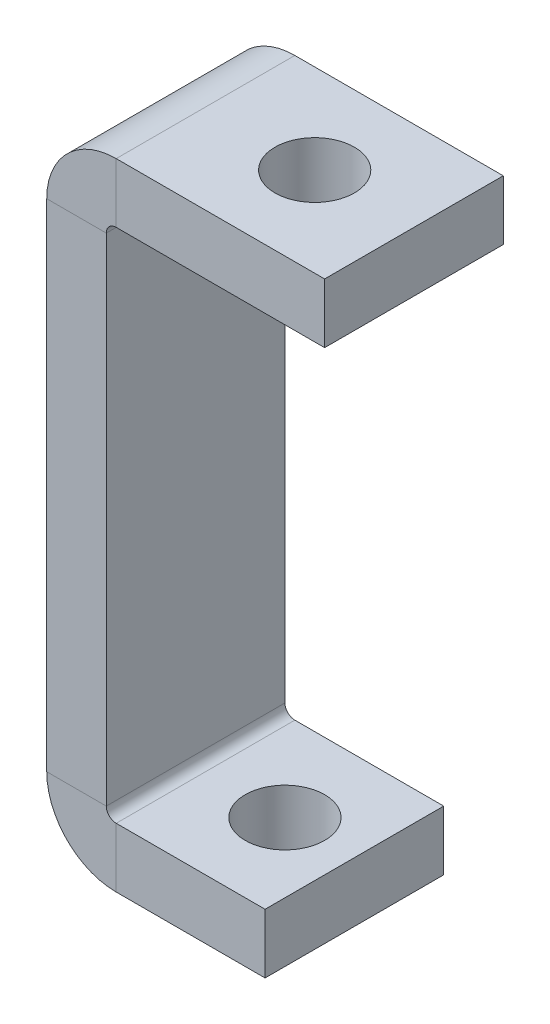
SolidWorks part; units mm, degrees
ref_plane "Front Plane" through (0, 0, 0) normal (0, 0, 1) x (1, 0, 0)
ref_plane "Top Plane" through (0, 0, 0) normal (0, 1, 0) x (1, 0, 0)
ref_plane "Right Plane" through (0, 0, 0) normal (1, 0, 0) x (0, 0, -1)
sketch "Sketch1" plane through (0, 0, 0) normal (0, 0, 1) x (1, 0, 0)
  line L0 (0, 0) -> (-7.5, 0)
  line L1 (-8, 0.5) -> (-8, 25.5)
  line L2 (-7.5, 26) -> (3, 26)
  arc A0 (-7.5, 0) -> (-8, 0.5) centre (-7.5, 0.5) cw
  arc A1 (-8, 25.5) -> (-7.5, 26) centre (-7.5, 25.5) cw
  point P7 (-8, 0)
  point P11 (-8, 26)
  dimension "D4" = 0.5
  dimension "D1" = 8
  dimension "D2" = 11
  dimension "D3" = 26
sketch "Sketch2" plane through (0, 0, 0) normal (1, 0, 0) x (0, 0, -1)
  line L1 (-4.5, 0) -> (4.5, 0)
  line L2 (-4.5, 0) -> (-4.5, -3)
  line L3 (-4.5, -3) -> (4.5, -3)
  line L4 (4.5, 0) -> (4.5, -3)
  dimension "D1" = 9
  dimension "D2" = 3
sweep "Sweep1" add profiles "Sketch2" path "Sketch1"
sketch "Sketch7" plane through (0, 29, 0) normal (0, 1, 0) x (1, 0, 0)
  line L0 (3, 0) -> (-11, 0) construction
  line L1 (3, -4.5) -> (3, 4.5) construction
  line L2 (-11, -4.5) -> (-11, 4.5) construction
  circle A0 centre (-2, 0) radius 2
  dimension "D1" = 4
  dimension "D2" = 9
extrude "Cut-Extrude1" cut sketch "Sketch7" against normal blind 10
sketch "Sketch8" plane through (0, -3, 0) normal (0, -1, 0) x (-1, 0, 0)
  line L0 (0, 0) -> (11, 0) construction
  line L1 (11, -4.5) -> (11, 4.5) construction
  circle A0 centre (3.5, 0) radius 2
  dimension "D1" = 4
  dimension "D2" = 7.5
extrude "Cut-Extrude2" cut sketch "Sketch8" against normal blind 10
